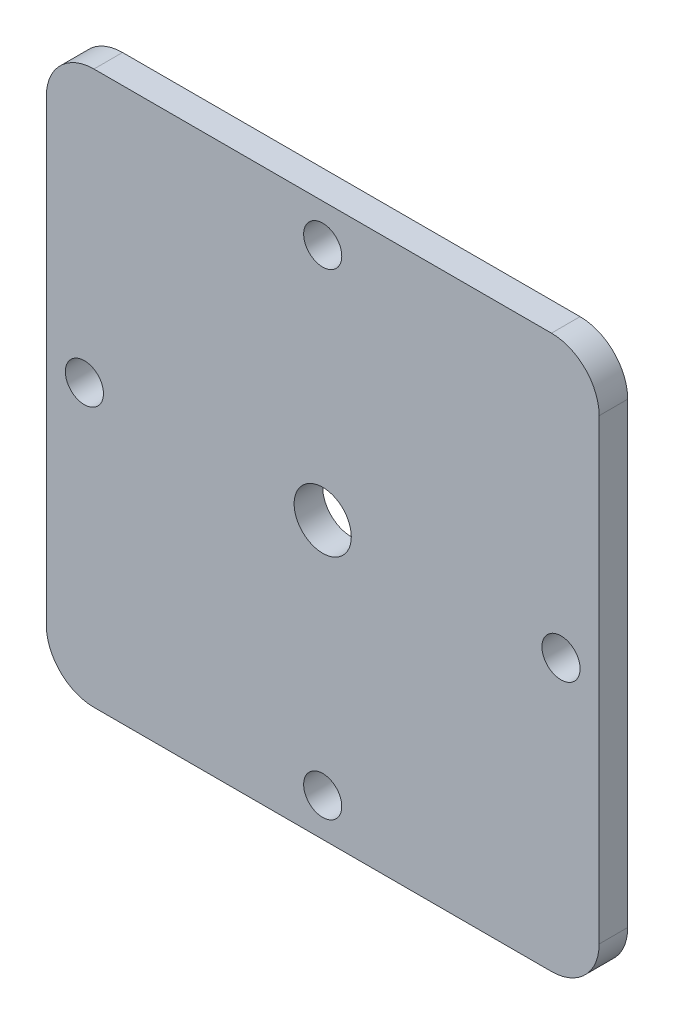
SolidWorks part; units mm, degrees
ref_plane "Спереди" through (0, 0, 0) normal (0, 0, 1) x (1, 0, 0)
ref_plane "Сверху" through (0, 0, 0) normal (0, 1, 0) x (1, 0, 0)
ref_plane "Справа" through (0, 0, 0) normal (1, 0, 0) x (0, 0, -1)
sketch "Эскиз1" plane through (0, 0, 0) normal (0, 0, 1) x (1, 0, 0)
  line L0 (0, 29) -> (0, -29) construction
  line L1 (-29, -29) -> (29, -29)
  line L2 (-29, -29) -> (-29, 29)
  line L3 (-29, 29) -> (29, 29)
  line L4 (29, -29) -> (29, 29)
  line L5 (-29, -29) -> (29, 29) construction
  line L6 (-29, 29) -> (29, -29) construction
  line L7 (-29, 0) -> (29, 0) construction
  circle A0 centre (0, 25) radius 2
  circle A1 centre (-25, 0) radius 2
  circle A2 centre (0, -25) radius 2
  circle A3 centre (25, 0) radius 2
  point P0 (0, 0)
  dimension "D1" = 4
  dimension "D2" = 4
  dimension "D4" = 4
  dimension "D5" = 4
  dimension "D3" = 58
extrude "Бобышка-Вытянуть1" add sketch "Эскиз1" along normal blind 3
fillet "Скругление2" radius 5 1 edges at (29, -29, 1.5)
fillet "Скругление3" radius 5 1 edges at (-29, -29, 1.5)
fillet "Скругление4" radius 5 1 edges at (-29, 29, 1.5)
fillet "Скругление5" radius 5 1 edges at (29, 29, 1.5)
sketch "Эскиз2" plane through (0, 0, 3) normal (0, 0, 1) x (1, 0, 0)
  circle A0 centre (0, 0) radius 3
  dimension "D1" = 6
extrude "Вырез-Вытянуть1" cut sketch "Эскиз2" against normal blind 3
